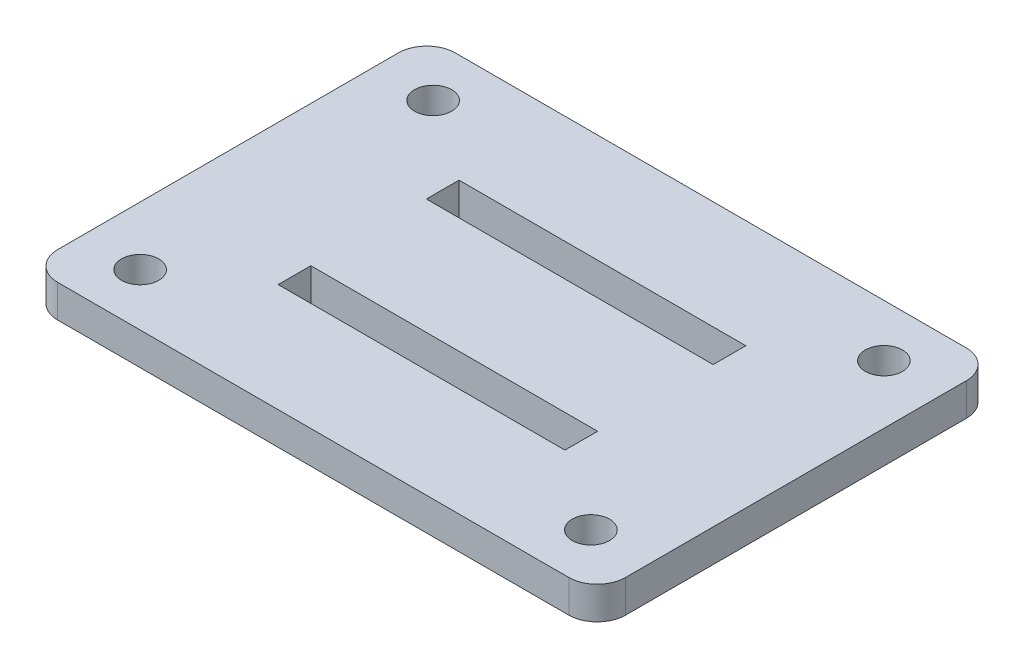
SolidWorks part; units mm, degrees
ref_plane "前视基准面" through (0, 0, 0) normal (0, 0, 1) x (1, 0, 0)
ref_plane "上视基准面" through (0, 0, 0) normal (0, 1, 0) x (1, 0, 0)
ref_plane "右视基准面" through (0, 0, 0) normal (1, 0, 0) x (0, 0, -1)
other "Configuration Table"
sketch "草图1" plane through (0, 0, 0) normal (0, 1, 0) x (1, 0, 0)
  line L0 (-89.3251, 0) -> (102.0425, 0) construction
  line L1 (0, 56.7239) -> (0, -62.578) construction
  line L2 (-20.2, -8.1375) -> (20.2, -8.1375)
  line L3 (-20.2, 12.7375) -> (20.2, 12.7375)
  line L4 (-20.2, 12.7375) -> (-20.2, 8.1375)
  line L5 (-20.2, 8.1375) -> (20.2, 8.1375)
  line L6 (20.2, 12.7375) -> (20.2, 8.1375)
  line L7 (-20.2, 12.7375) -> (20.2, 8.1375) construction
  line L8 (-20.2, 8.1375) -> (20.2, 12.7375) construction
  line L9 (20.2, -12.7375) -> (20.2, -8.1375)
  line L10 (-20.2, -12.7375) -> (20.2, -12.7375)
  line L11 (-20.2, -12.7375) -> (-20.2, -8.1375)
  circle A0 centre (-31.75, 20.6375) radius 2.625
  circle A4 centre (31.75, 20.6375) radius 2.625
  circle A5 centre (31.75, -20.6375) radius 2.625
  circle A6 centre (-31.75, -20.6375) radius 2.625
  point P13 (0, 10.4375)
  dimension "D5" = 5.25
  dimension "D9" = 5.25
  dimension "D7" = 10.4375
  dimension "D1" = 40.4
  dimension "D2" = 31.75
  dimension "D3" = 4.6
  dimension "D4" = 20.6375
  dimension "D8" = 4.6
  dimension "D10" = 40.4
  dimension "D11" = 7.9
  dimension "D12" = 31.75
sketch "草图3" plane through (0, 0, 0) normal (0, 1, 0) x (1, 0, 0)
  line L1 (-40, -28) -> (40, -28)
  line L2 (-40, -28) -> (-40, 28)
  line L3 (-40, 28) -> (40, 28)
  line L4 (40, -28) -> (40, 28)
  line L5 (-40, -28) -> (40, 28) construction
  line L6 (-40, 28) -> (40, -28) construction
  point P0 (0, 0)
  dimension "D1" = 56
  dimension "D2" = 80
extrude "凸台-拉伸1" add sketch "草图3" along normal blind 4.6
extrude "切除-拉伸1" cut sketch "草图1" along normal up to surface (4.6 mm away) up to face at (0, 4.6, 0)
fillet "圆角2" radius 4 4 edges at (-40, 2.3, -28) (40, 2.3, -28) (40, 2.3, 28) (-40, 2.3, 28)
